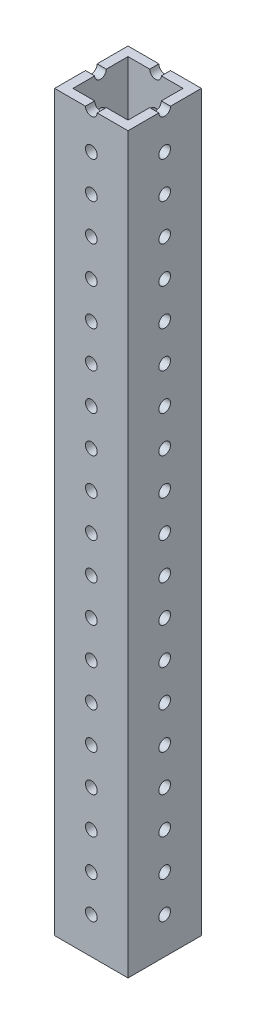
SolidWorks part; units mm, degrees
material "3003 Alloy"
ref_plane "Front Plane" through (0, 0, 0) normal (0, 0, 1) x (1, 0, 0)
ref_plane "Top Plane" through (0, 0, 0) normal (0, 1, 0) x (1, 0, 0)
ref_plane "Right Plane" through (0, 0, 0) normal (1, 0, 0) x (0, 0, -1)
sketch "Sketch1" plane through (0, 0, 0) normal (0, 1, 0) x (1, 0, 0)
  line L0 (3.175, 22.225) -> (22.225, 22.225)
  line L1 (0, 0) -> (25.4, 0)
  line L2 (0, 0) -> (0, 25.4)
  line L3 (0, 25.4) -> (25.4, 25.4)
  line L4 (25.4, 0) -> (25.4, 25.4)
  line L5 (22.225, 3.175) -> (22.225, 22.225)
  line L6 (3.175, 3.175) -> (22.225, 3.175)
  line L7 (3.175, 3.175) -> (3.175, 22.225)
  dimension "D1" = 25.4
  dimension "D2" = 25.4
  dimension "D3" = 3.175
extrude "Boss-Extrude1" add sketch "Sketch1" along normal blind 254
sketch "Sketch2" plane through (0, 0, 0) normal (0, 0, 1) x (1, 0, 0)
  line L0 (0, 0) -> (25.4, 0) construction
  line L1 (0, 254) -> (0, 0) construction
  circle A0 centre (12.7, 12.7) radius 2.0193
  circle A1 centre (12.7, 25.4) radius 2.0193
  circle A2 centre (12.7, 38.1) radius 2.0193
  circle A3 centre (12.7, 50.8) radius 2.0193
  circle A4 centre (12.7, 63.5) radius 2.0193
  circle A5 centre (12.7, 76.2) radius 2.0193
  circle A6 centre (12.7, 88.9) radius 2.0193
  circle A7 centre (12.7, 101.6) radius 2.0193
  circle A8 centre (12.7, 114.3) radius 2.0193
  circle A9 centre (12.7, 127) radius 2.0193
  circle A10 centre (12.7, 139.7) radius 2.0193
  circle A11 centre (12.7, 152.4) radius 2.0193
  circle A12 centre (12.7, 165.1) radius 2.0193
  circle A13 centre (12.7, 177.8) radius 2.0193
  circle A14 centre (12.7, 190.5) radius 2.0193
  circle A15 centre (12.7, 203.2) radius 2.0193
  circle A16 centre (12.7, 215.9) radius 2.0193
  circle A17 centre (12.7, 228.6) radius 2.0193
  circle A18 centre (12.7, 241.3) radius 2.0193
  circle A19 centre (12.7, 254) radius 2.0193
  circle A20 centre (12.7, 266.7) radius 2.0193
  circle A21 centre (12.7, 279.4) radius 2.0193
  circle A22 centre (12.7, 292.1) radius 2.0193
  circle A23 centre (12.7, 304.8) radius 2.0193
  circle A24 centre (12.7, 317.5) radius 2.0193
  circle A25 centre (12.7, 330.2) radius 2.0193
  circle A26 centre (12.7, 342.9) radius 2.0193
  circle A27 centre (12.7, 355.6) radius 2.0193
  circle A28 centre (12.7, 368.3) radius 2.0193
  circle A29 centre (12.7, 381) radius 2.0193
  circle A30 centre (12.7, 393.7) radius 2.0193
  circle A31 centre (12.7, 406.4) radius 2.0193
  circle A32 centre (12.7, 419.1) radius 2.0193
  circle A33 centre (12.7, 431.8) radius 2.0193
  circle A34 centre (12.7, 444.5) radius 2.0193
  circle A35 centre (12.7, 457.2) radius 2.0193
  circle A36 centre (12.7, 469.9) radius 2.0193
  circle A37 centre (12.7, 482.6) radius 2.0193
  circle A38 centre (12.7, 495.3) radius 2.0193
  circle A39 centre (12.7, 508) radius 2.0193
  circle A40 centre (12.7, 520.7) radius 2.0193
  circle A41 centre (12.7, 533.4) radius 2.0193
  circle A42 centre (12.7, 546.1) radius 2.0193
  circle A43 centre (12.7, 558.8) radius 2.0193
  circle A44 centre (12.7, 571.5) radius 2.0193
  circle A45 centre (12.7, 584.2) radius 2.0193
  circle A46 centre (12.7, 596.9) radius 2.0193
  circle A47 centre (12.7, 609.6) radius 2.0193
  circle A48 centre (12.7, 622.3) radius 2.0193
  dimension "D3" = 4.0386
  dimension "D1" = 12.7
  dimension "D2" = 12.7
  dimension "D4" = 49
extrude "Cut-Extrude1" cut sketch "Sketch2" against normal blind 635
sketch "Sketch3" plane through (25.4, 0, 0) normal (1, 0, 0) x (0, 0, -1)
  line L0 (0, 254) -> (0, 0) construction
  line L1 (0, 0) -> (25.4, 0) construction
  circle A0 centre (12.7, 12.7) radius 2.0193
  circle A1 centre (12.7, 25.4) radius 2.0193
  circle A2 centre (12.7, 38.1) radius 2.0193
  circle A3 centre (12.7, 50.8) radius 2.0193
  circle A4 centre (12.7, 63.5) radius 2.0193
  circle A5 centre (12.7, 76.2) radius 2.0193
  circle A6 centre (12.7, 88.9) radius 2.0193
  circle A7 centre (12.7, 101.6) radius 2.0193
  circle A8 centre (12.7, 114.3) radius 2.0193
  circle A9 centre (12.7, 127) radius 2.0193
  circle A10 centre (12.7, 139.7) radius 2.0193
  circle A11 centre (12.7, 152.4) radius 2.0193
  circle A12 centre (12.7, 165.1) radius 2.0193
  circle A13 centre (12.7, 177.8) radius 2.0193
  circle A14 centre (12.7, 190.5) radius 2.0193
  circle A15 centre (12.7, 203.2) radius 2.0193
  circle A16 centre (12.7, 215.9) radius 2.0193
  circle A17 centre (12.7, 228.6) radius 2.0193
  circle A18 centre (12.7, 241.3) radius 2.0193
  circle A19 centre (12.7, 254) radius 2.0193
  circle A20 centre (12.7, 266.7) radius 2.0193
  circle A21 centre (12.7, 279.4) radius 2.0193
  circle A22 centre (12.7, 292.1) radius 2.0193
  circle A23 centre (12.7, 304.8) radius 2.0193
  circle A24 centre (12.7, 317.5) radius 2.0193
  circle A25 centre (12.7, 330.2) radius 2.0193
  circle A26 centre (12.7, 342.9) radius 2.0193
  circle A27 centre (12.7, 355.6) radius 2.0193
  circle A28 centre (12.7, 368.3) radius 2.0193
  circle A29 centre (12.7, 381) radius 2.0193
  circle A30 centre (12.7, 393.7) radius 2.0193
  circle A31 centre (12.7, 406.4) radius 2.0193
  circle A32 centre (12.7, 419.1) radius 2.0193
  circle A33 centre (12.7, 431.8) radius 2.0193
  circle A34 centre (12.7, 444.5) radius 2.0193
  circle A35 centre (12.7, 457.2) radius 2.0193
  circle A36 centre (12.7, 469.9) radius 2.0193
  circle A37 centre (12.7, 482.6) radius 2.0193
  circle A38 centre (12.7, 495.3) radius 2.0193
  circle A39 centre (12.7, 508) radius 2.0193
  circle A40 centre (12.7, 520.7) radius 2.0193
  circle A41 centre (12.7, 533.4) radius 2.0193
  circle A42 centre (12.7, 546.1) radius 2.0193
  circle A43 centre (12.7, 558.8) radius 2.0193
  circle A44 centre (12.7, 571.5) radius 2.0193
  circle A45 centre (12.7, 584.2) radius 2.0193
  circle A46 centre (12.7, 596.9) radius 2.0193
  circle A47 centre (12.7, 609.6) radius 2.0193
  circle A48 centre (12.7, 622.3) radius 2.0193
  dimension "D3" = 4.0386
  dimension "D1" = 12.7
  dimension "D2" = 12.7
  dimension "D4" = 49
extrude "Cut-Extrude2" cut sketch "Sketch3" against normal blind 635
